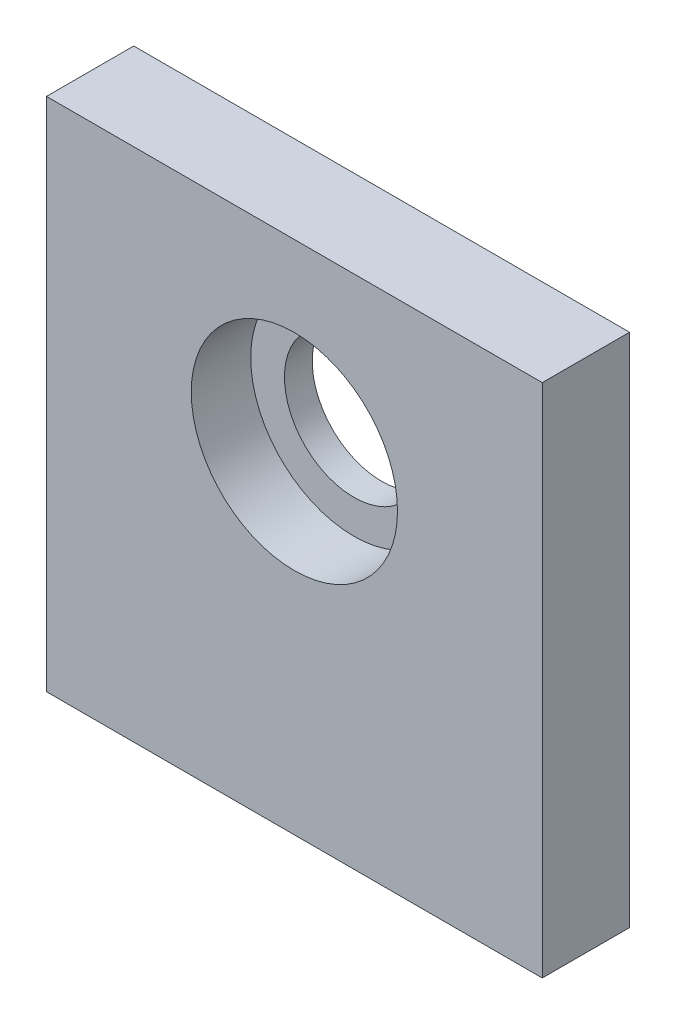
SolidWorks part; units mm, degrees
ref_plane "Front" through (0, 0, 0) normal (0, 0, 1) x (1, 0, 0)
ref_plane "Top" through (0, 0, 0) normal (0, 1, 0) x (1, 0, 0)
ref_plane "Right" through (0, 0, 0) normal (1, 0, 0) x (0, 0, -1)
sketch "Sketch1" plane through (0, 0, 0) normal (0, 0, 1) x (1, 0, 0)
  line L0 (0, -9.0468) -> (0, 151.1803) construction
  line L1 (-62.5, 130) -> (62.5, 130)
  line L2 (-62.5, 130) -> (-62.5, 0)
  line L3 (-62.5, 0) -> (62.5, 0)
  line L4 (62.5, 130) -> (62.5, 0)
  dimension "D1" = 130
  dimension "D2" = 125
extrude "Boss-Extrude1" add sketch "Sketch1" against normal blind 22
sketch "Sketch2" plane through (0, 0, 0) normal (1, 0, 0) x (0, 0, -1)
  line L0 (-6.0881, 83.7) -> (32.9444, 83.7) construction
  line L2 (0, 109.7) -> (15, 109.7)
  line L3 (15, 109.7) -> (15, 101.2)
  line L4 (15, 101.2) -> (22, 101.2)
  line L5 (0, 83.7) -> (22, 83.7)
  line L7 (0, 0) -> (0, 130) construction
  line L9 (22, 0) -> (0, 0) construction
  line L10 (22, 0) -> (22, 130) construction
  line L11 (22, 101.2) -> (22, 83.7)
  line L12 (0, 109.7) -> (0, 83.7)
  dimension "D1" = 83.7
  dimension "D2" = 35
  dimension "D3" = 52
  dimension "D4" = 15
revolve "Cut-Revolve1" cut sketch "Sketch2" angle 360 about L0
hole_wizard "M5x0.8 Tapped Hole1" positions "Sketch5" profile "Sketch4" tap size "M5x0.8" standard "JIS"
sketch "Sketch5" plane through (0, 0, 0) normal (0, -1, 0) x (1, 0, 0)
  line L0 (0, 3.6519) -> (0, -25.797) construction
  line L2 (-62.5, 0) -> (62.5, 0) construction
  point P0 (-50, -11)
  point P1 (50, -11)
  dimension "D1" = 100
  dimension "D2" = 11
sketch "Sketch4" plane through (-50, 0, -11) normal (1, 0, 0) x (0, 0, -1)
  line L0 (0, 0) -> (0, 15.2618)
  line L1 (0, 15.2618) -> (2.1, 14)
  line L2 (2.1, 14) -> (2.1, 0)
  line L5 (2.1, 0) -> (0, 0)
  line L10 (0, 15.2618) -> (-2.1, 14) construction
  line L11 (0, -6.35) -> (0, 107.95) construction
  dimension "Tap Drill Dia." = 4.2
  dimension "Tap Drill Depth" = 14
  dimension "Drill Angle" = 118
cosmetic thread "Hole Thread1" parameters "D1"=10, "D2"=5
cosmetic thread "Hole Thread2" parameters "D1"=10, "D2"=5
